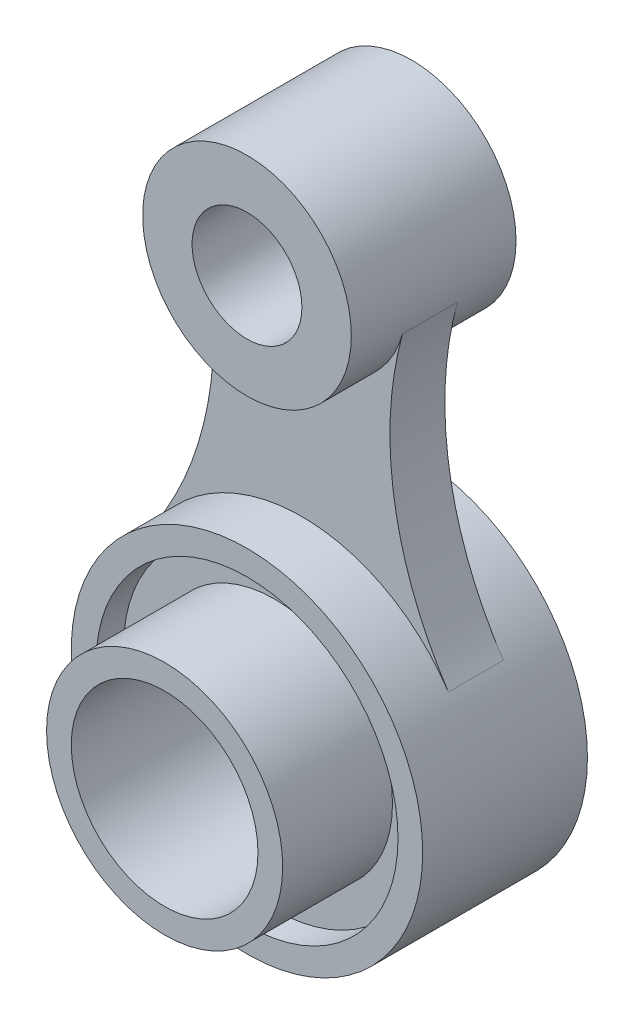
SolidWorks part; units mm, degrees
material "1060 Alloy"
ref_plane "Front Plane" through (0, 0, 0) normal (0, 0, 1) x (1, 0, 0)
ref_plane "Top Plane" through (0, 0, 0) normal (0, 1, 0) x (1, 0, 0)
ref_plane "Right Plane" through (0, 0, 0) normal (1, 0, 0) x (0, 0, -1)
sketch "Esquisse4" plane through (0, 0, 0) normal (0, 0, 1) x (1, 0, 0)
  circle A0 centre (0, 0) radius 32
  circle A1 centre (0, 0) radius 17
  circle A2 centre (0, 75) radius 10
  circle A3 centre (0, 75) radius 19
  dimension "D1" = 64
  dimension "D2" = 34
  dimension "D3" = 38
  dimension "D4" = 20
  dimension "D5" = 75
extrude "Boss.-Extru.3" add sketch "Esquisse4" along normal mid plane 30
sketch "Esquisse6" plane through (0, 0, 15) normal (0, 0, 1) x (1, 0, 0)
  circle A0 centre (0, 0) radius 27.5
  circle A1 centre (0, 0) radius 21.5
  dimension "D1" = 55
  dimension "D2" = 43
extrude "Enlèv. mat.-Extru.2" cut sketch "Esquisse6" against normal blind 5 contours A1 | A0
sketch "Esquisse11" plane through (0, 0, 15) normal (0, 0, 1) x (1, 0, 0)
  circle A0 centre (0, 0) radius 17 construction
  circle A2 centre (0, 0) radius 21.5 construction
  circle A3 centre (0, 0) radius 17
  circle A4 centre (0, 0) radius 21.5
extrude "Boss.-Extru.4" add sketch "Esquisse11" along normal blind 15
sketch "Esquisse13" plane through (0, 0, 0) normal (0, 0, 1) x (1, 0, 0)
  arc A0 (-18.3212, 69.9669) -> (18.3212, 69.9669) centre (0, 75) ccw
  circle A1 centre (0, 75) radius 19 construction
  arc A2 (26.6783, 17.6711) -> (-26.6783, 17.6711) centre (0, 0) ccw
  circle A3 centre (0, 0) radius 32 construction
  arc A4 (18.3212, 69.9669) -> (26.6783, 17.6711) centre (80.0349, 53.0133) ccw
  arc A5 (-26.6783, 17.6711) -> (-18.3212, 69.9669) centre (-80.0349, 53.0133) ccw
  dimension "D1" = 64
  dimension "D2" = 64
extrude "Boss.-Extru.5" add sketch "Esquisse13" along normal mid plane 10
